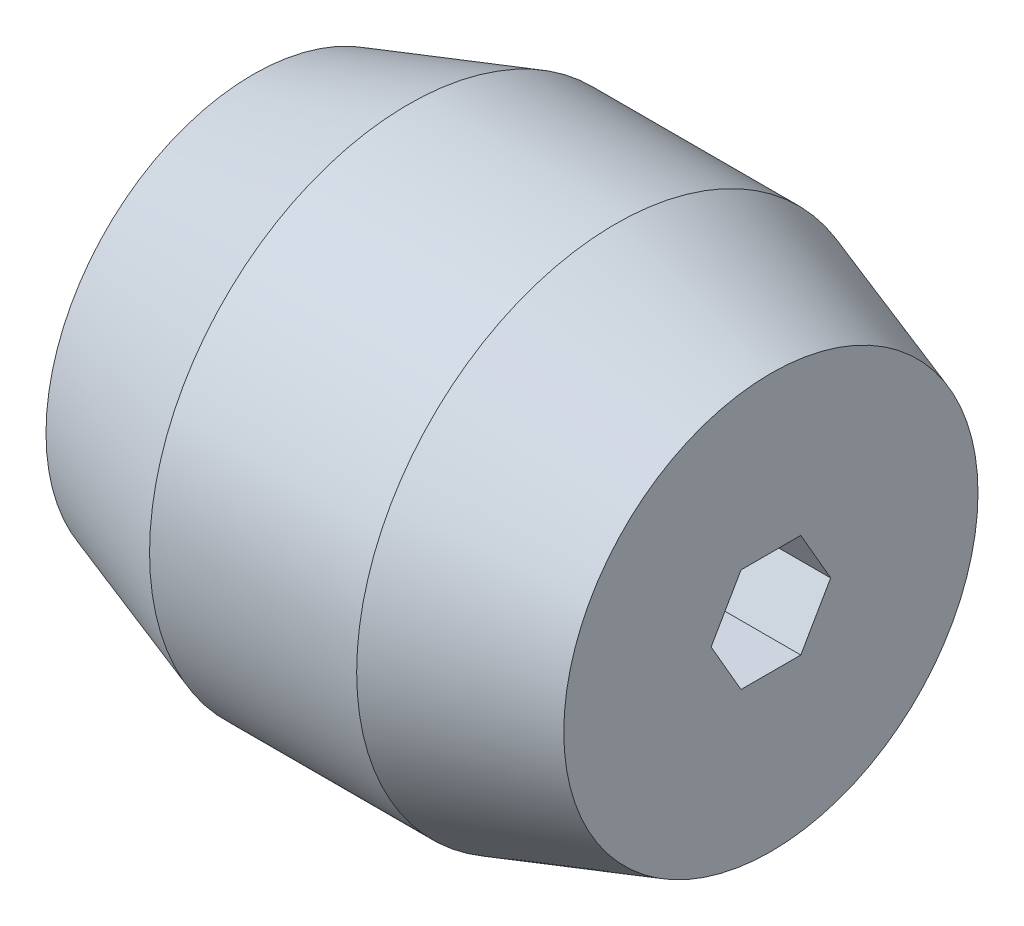
SolidWorks part; units mm, degrees
material "6061 Alloy"
ref_plane "Front Plane" through (0, 0, 0) normal (0, 0, 1) x (1, 0, 0)
ref_plane "Top Plane" through (0, 0, 0) normal (0, 1, 0) x (1, 0, 0)
ref_plane "Right Plane" through (0, 0, 0) normal (1, 0, 0) x (0, 0, -1)
sketch "Sketch1" plane through (0, 0, 0) normal (0, 0, 1) x (1, 0, 0)
  line L0 (0, 0) -> (63.5, 0)
  line L1 (63.5, 0) -> (63.5, 25.4)
  line L2 (63.5, 25.4) -> (44.45, 31.75)
  line L3 (44.45, 31.75) -> (19.05, 31.75)
  line L4 (19.05, 31.75) -> (0, 25.4)
  line L5 (0, 25.4) -> (0, 0)
  dimension "D1" = 25.4
  dimension "D2" = 31.75
  dimension "D3" = 25.4
  dimension "D4" = 63.5
  dimension "D5" = 19.05
revolve "Revolve1" add sketch "Sketch1" angle 360 about L0
sketch "Sketch2" plane through (0, 0, 0) normal (-1, 0, 0) x (0, 0, 1)
  line L1 (-3.6662, 6.35) -> (-7.3323, 0)
  line L2 (-7.3323, 0) -> (-3.6662, -6.35)
  line L3 (-3.6662, -6.35) -> (3.6662, -6.35)
  line L4 (3.6662, -6.35) -> (7.3323, 0)
  line L5 (7.3323, 0) -> (3.6662, 6.35)
  line L6 (3.6662, 6.35) -> (-3.6662, 6.35)
  circle A0 centre (0, 0) radius 6.35 construction
  dimension "D1" = 12.7
extrude "Cut-Extrude1" cut sketch "Sketch2" against normal through all both and the other way through all
